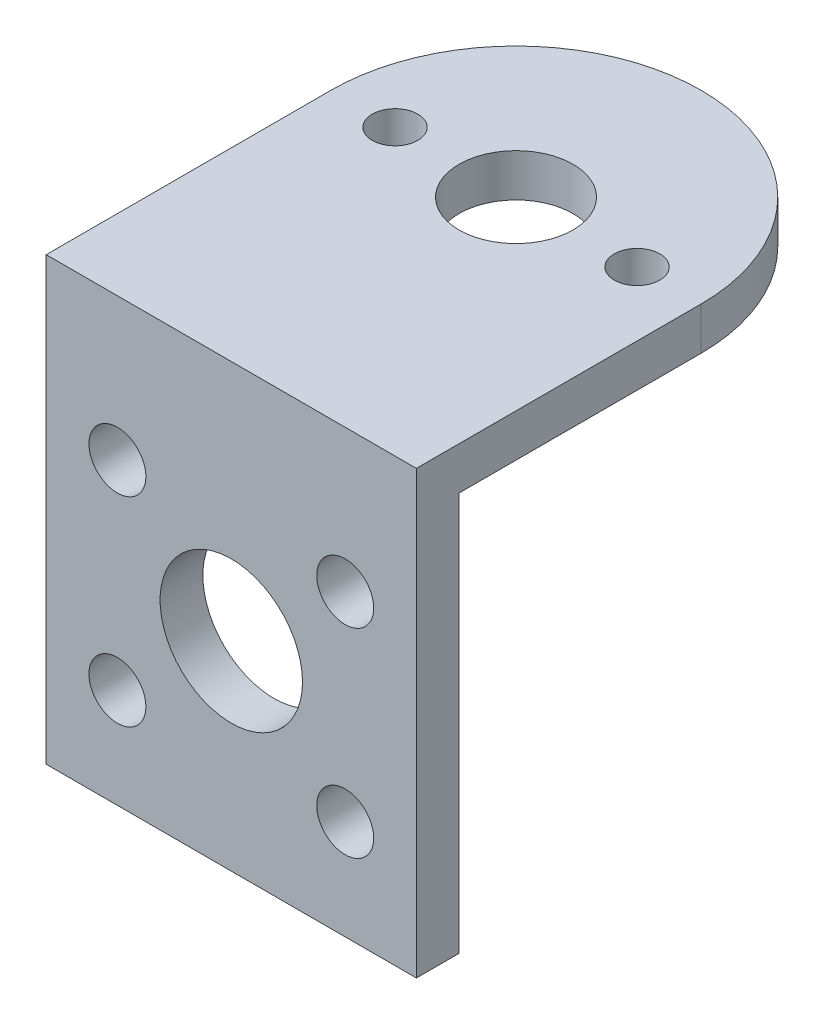
SolidWorks part; units mm, degrees
material "1060-H16"
ref_plane "前视基准面" through (0, 0, 0) normal (0, 0, 1) x (1, 0, 0)
ref_plane "上视基准面" through (0, 0, 0) normal (0, 1, 0) x (1, 0, 0)
ref_plane "右视基准面" through (0, 0, 0) normal (1, 0, 0) x (0, 0, -1)
sketch "草图1" plane through (0, 0, 0) normal (0, 1, 0) x (1, 0, 0)
  line L0 (-22.1192, 0) -> (31.5102, 0) construction
  line L1 (-13, 0) -> (-13, -20)
  line L2 (-13, -20) -> (13, -20)
  line L3 (13, -20) -> (13, 0)
  circle A0 centre (0, 0) radius 4
  arc A1 (13, 0) -> (-13, 0) centre (0, 0) ccw
  circle A2 centre (-8.5, 0) radius 1.6
  circle A3 centre (8.5, 0) radius 1.6
  dimension "D1" = 8
  dimension "D2" = 26
  dimension "D4" = 3.2
  dimension "D5" = 3.2
  dimension "D6" = 90
  dimension "D7" = 20
  dimension "D3" = 17
  dimension "D8" = 8.5
extrude "凸台-拉伸1" add sketch "草图1" along normal blind 3
sketch "草图3" plane through (0, 0, 20) normal (0, 0, 1) x (1, 0, 0)
  line L0 (-13, 3) -> (-13, -28)
  line L1 (-13, 3) -> (-13, 0) construction
  line L2 (-13, 3) -> (13, 3) construction
  line L3 (-13, -28) -> (13, -28)
  line L4 (13, -28) -> (13, 3)
  line L5 (-23.5526, -14) -> (43.8151, -14) construction
  line L6 (43.8151, -14) -> (0, -14) construction
  line L7 (0, -14) -> (0, 6.2291) construction
  line L8 (0, 6.2291) -> (0, -32.9344) construction
  line L9 (-13, 3) -> (13, 3)
  line L10 (-13, 0) -> (13, 0) construction
  circle A0 centre (0, -14) radius 5
  circle A1 centre (-8, -7) radius 2
  circle A2 centre (8, -7) radius 2
  circle A3 centre (8, -21) radius 2
  circle A4 centre (-8, -21) radius 2
  dimension "D4" = 10
  dimension "D7" = 4
  dimension "D8" = 4
  dimension "D9" = 4
  dimension "D10" = 4
  dimension "D2" = 26
  dimension "D3" = 31
  dimension "D5" = 16
  dimension "D6" = 14
  dimension "D11" = 7
  dimension "D12" = 8
  dimension "D13" = 14
  dimension "D14" = 7
  dimension "D15" = 8
  dimension "D16" = 8
  dimension "D17" = 7
  dimension "D18" = 14
extrude "凸台-拉伸2" add sketch "草图3" against normal blind 3
